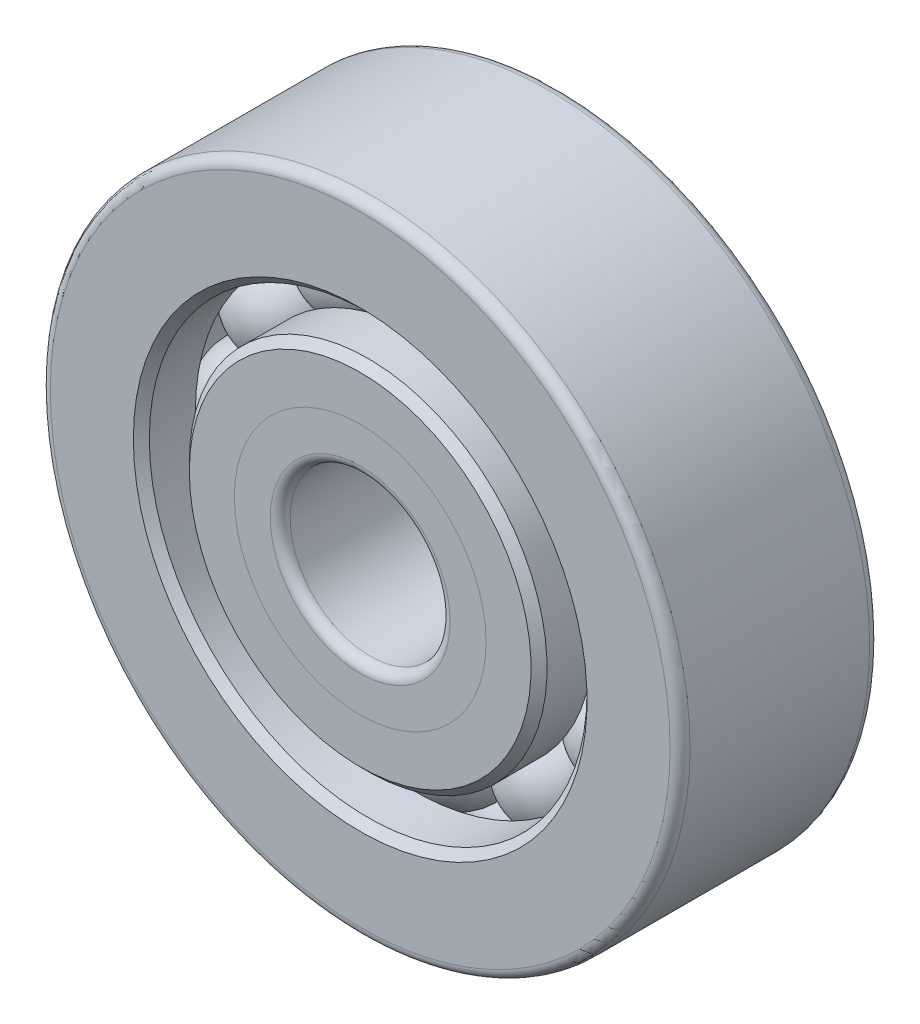
SolidWorks part; units mm, degrees
ref_plane "Front Plane" through (0, 0, 0) normal (0, 0, 1) x (1, 0, 0)
ref_plane "Top Plane" through (0, 0, 0) normal (0, 1, 0) x (1, 0, 0)
ref_plane "Right Plane" through (0, 0, 0) normal (1, 0, 0) x (0, 0, -1)
sketch "Sketch1" plane through (0, 0, 0) normal (1, 0, 0) x (0, 0, -1)
  line L0 (-3.9624, 0) -> (3.9624, 0) construction
  line L9 (0, 12.7) -> (0, 0) construction
  line L10 (-3.9624, 3.175) -> (3.9624, 3.175)
  line L11 (3.9624, 3.175) -> (3.9624, 7.1016)
  line L12 (3.9624, 7.1016) -> (-3.9624, 7.1016)
  line L13 (-3.9624, 7.1016) -> (-3.9624, 3.175)
  line L14 (-3.9624, 8.6896) -> (3.9624, 8.6896)
  line L15 (3.9624, 8.6896) -> (3.9624, 12.7)
  line L16 (3.9624, 12.7) -> (-3.9624, 12.7)
  line L17 (-3.9624, 12.7) -> (-3.9624, 8.6896)
  line L18 (-1.985, 7.8956) -> (1.985, 7.8956) construction
  line L20 (3.9624, 4.9987) -> (-3.9624, 4.9987) construction
  line L21 (0, 5.9106) -> (0, 4.9987)
  line L22 (0, 4.9987) -> (0, 4.0869)
  line L23 (0, 4.0869) -> (0, 3.175)
  circle A0 centre (0, 7.8956) radius 1.985
  point P17 (0, 9.8806)
  dimension "ID" = 6.35
  dimension "OD" = 25.4
  dimension "Ball Diameter" = 3.97
  dimension "Ball Pattern Diameter" = 15.7912
  dimension "D6" = 1.588
  dimension "Width" = 7.9248
sketch "Sketch2" plane through (0, 0, 0) normal (0, 0, 1) x (1, 0, 0)
  circle A0 centre (0, 0) radius 7.8956 construction
  circle A1 centre (0, 7.8956) radius 1.985
  circle A2 centre (3.9478, 6.8378) radius 1.985
  circle A3 centre (6.8378, 3.9478) radius 1.985
  circle A4 centre (7.8956, 0) radius 1.985
  circle A5 centre (6.8378, -3.9478) radius 1.985
  circle A6 centre (3.9478, -6.8378) radius 1.985
  circle A7 centre (0, -7.8956) radius 1.985
  circle A8 centre (-3.9478, -6.8378) radius 1.985
  circle A9 centre (-6.8378, -3.9478) radius 1.985
  circle A10 centre (-7.8956, 0) radius 1.985
  circle A11 centre (-6.8378, 3.9478) radius 1.985
  circle A12 centre (-3.9478, 6.8378) radius 1.985
  circle A15 centre (0, 0) radius 3.175 construction
  circle A16 centre (0, 0) radius 12.7 construction
  point P36 (0, 0)
  dimension "ID" = 6.35
  dimension "OD" = 25.4
  dimension "No. of Balls" = 12
sketch "Sketch3" plane through (0, 0, 0) normal (1, 0, 0) x (0, 0, -1)
  line L1 (3.9624, 3.175) -> (3.9624, 7.1016) construction
  line L2 (-3.9624, 7.1016) -> (-3.9624, 3.175) construction
  line L3 (3.9624, 7.1016) -> (-3.9624, 7.1016) construction
  line L5 (3.9624, 3.175) -> (3.9624, 7.1016)
  line L6 (-3.9624, 7.1016) -> (-3.9624, 3.175)
  line L7 (3.9624, 7.1016) -> (-3.9624, 7.1016)
  line L8 (-3.9624, 12.7) -> (-3.9624, 8.6896) construction
  line L9 (3.9624, 12.7) -> (-3.9624, 12.7) construction
  line L10 (3.9624, 8.6896) -> (3.9624, 12.7) construction
  line L11 (-3.9624, 8.6896) -> (3.9624, 8.6896) construction
  line L12 (-3.9624, 12.7) -> (-3.9624, 8.6896)
  line L13 (3.9624, 12.7) -> (-3.9624, 12.7)
  line L14 (3.9624, 8.6896) -> (3.9624, 12.7)
  line L15 (-3.9624, 8.6896) -> (3.9624, 8.6896)
  line L16 (-3.9624, 3.175) -> (3.9624, 3.175) construction
  line L17 (-3.9624, 3.175) -> (3.9624, 3.175)
revolve "Revolve2" add sketch "Sketch3" angle 360 about L0
sketch "Sketch4" plane through (0, 0, 0) normal (1, 0, 0) x (0, 0, -1)
  circle A0 centre (0, 7.8956) radius 1.985 construction
  circle A1 centre (0, 7.8956) radius 1.985
revolve "Cut-Revolve1" cut sketch "Sketch4" angle 360 about L0
sketch "Sketch5" plane through (0, 0, 0) normal (1, 0, 0) x (0, 0, -1)
  line L0 (-1.985, 7.8956) -> (1.985, 7.8956) construction
  line L1 (-1.985, 7.8956) -> (1.985, 7.8956)
  circle A0 centre (0, 7.8956) radius 1.985 construction
  arc A1 (1.985, 7.8956) -> (-1.985, 7.8956) centre (0, 7.8956) ccw
revolve "Revolve3" add sketch "Sketch5" angle 360 about L18
pattern_circular "CirPattern1" count 12 over 360 about axis through (0, 0, 0) along (0, 0, 1) of bodies 109
fillet "Fillet1" radius 0.3962 2 edges at (12.7, 0, 3.9624) (12.7, 0, -3.9624)
fillet "Fillet2" radius 0.3962 2 edges at (3.175, 0, -3.9624) (3.175, 0, 3.9624)
chamfer "Chamfer1" distance 0.317 angle 45 2 edges at (8.6896, 0, -3.9624) (8.6896, 0, 3.9624)
chamfer "Chamfer2" distance 0.317 angle 45 2 edges at (7.1016, 0, 3.9624) (7.1016, 0, -3.9624)
sketch "Split Line" plane through (0, 0, 0) normal (0, 0, 1) x (1, 0, 0)
  circle A0 centre (0, 0) radius 4.9987
split "Split1" trim tools "Split Line" bodies to split 108 resulting bodies 128 129
equation "\"D1@CirPattern1\"=\"No. of Balls@Sketch2\""
equation "\"D6@Sketch1\"=\"Ball Diameter@Sketch1\"*0.4"
equation "\"D1@Fillet1\"=\"Width@Sketch1\"/20"
equation "\"D1@Fillet2\"=\"Width@Sketch1\"/20"
equation "\"D1@Chamfer1\"=\"Width@Sketch1\"/25"
equation "\"D1@Chamfer2\"=\"Width@Sketch1\"/25"
equation "\"ID@Sketch2\"=\"ID@Sketch1\""
equation "\"OD@Sketch2\" = \"OD@Sketch1\""
